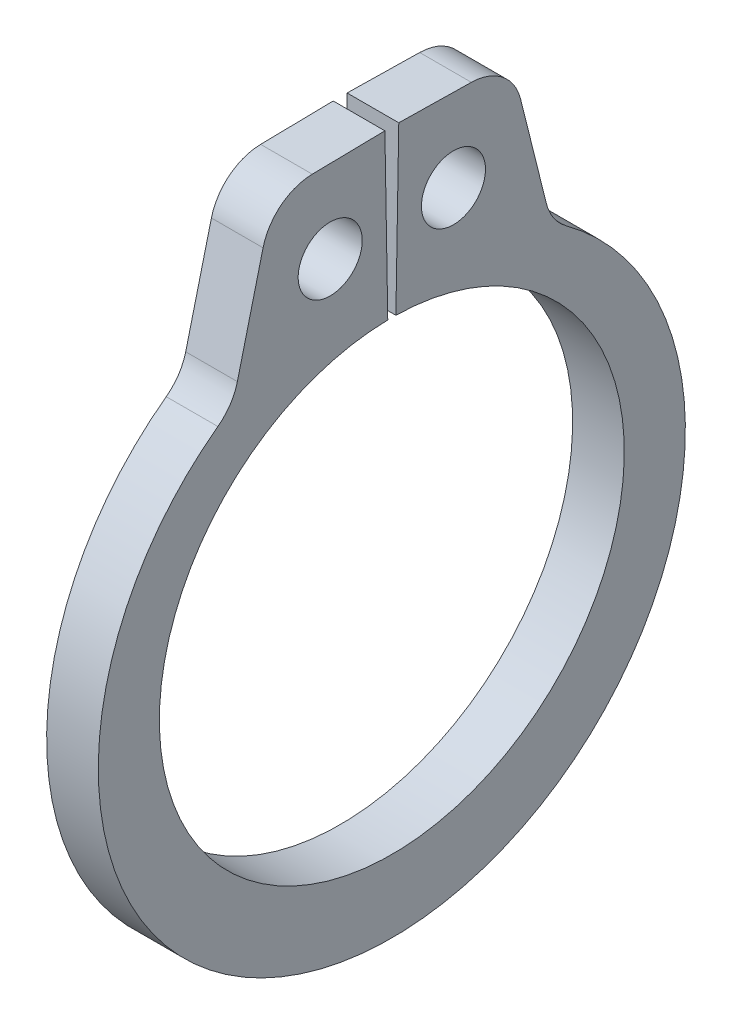
SolidWorks part; units mm, degrees
ref_plane "Front" through (0, 0, 0) normal (0, 0, 1) x (1, 0, 0)
ref_plane "Top" through (0, 0, 0) normal (0, 1, 0) x (1, 0, 0)
ref_plane "Right" through (0, 0, 0) normal (1, 0, 0) x (0, 0, -1)
sketch "Sketch1" plane through (0, 0, 0) normal (1, 0, 0) x (0, 0, -1)
  line L0 (0, 0) -> (0, 2.8575) construction
  line L1 (-0.0499, 2.8571) -> (-0.0853, 4.8888)
  line L2 (-0.0853, 4.8888) -> (-1.4649, 4.8647) construction
  line L3 (-1.4649, 4.8647) -> (-1.9565, 2.893) construction
  line L4 (0.0853, 4.8888) -> (0.0499, 2.8571)
  line L5 (0.0853, 4.8888) -> (1.4649, 4.8647) construction
  line L6 (1.4649, 4.8647) -> (1.9565, 2.893) construction
  line L7 (-1.9565, 2.893) -> (-1.6008, 2.367) construction
  line L8 (1.9565, 2.893) -> (1.6008, 2.367) construction
  line L9 (0, -2.8575) -> (0, -3.7465) construction
  line L10 (-1.4649, 4.8647) -> (-0.0499, 2.8571) construction
  line L11 (-2.8575, 0) -> (2.8575, 0) construction
  line L12 (0, 2.8575) -> (0, 4.8895) construction
  line L13 (1.4649, 4.8647) -> (1.9565, 2.893)
  line L14 (-1.4649, 4.8647) -> (-1.9565, 2.893)
  line L15 (0.0853, 4.8888) -> (1.4649, 4.8647)
  line L16 (-0.0853, 4.8888) -> (-1.4649, 4.8647)
  circle A0 centre (0, 0) radius 2.8575 construction
  arc A1 (-0.0499, 2.8571) -> (0.0499, 2.8571) centre (0, 0) ccw
  circle A2 centre (0, -0.1385) radius 3.608 construction
  circle A3 centre (0, 0) radius 4.699 construction
  circle A4 centre (-0.7574, 3.8609) radius 0.3937
  circle A5 centre (0.7574, 3.8609) radius 0.3937
  arc A6 (-1.9565, 2.893) -> (1.9565, 2.893) centre (0, -0.1385) ccw
  dimension "D1" = 15
  dimension "A" = 5.715
  dimension "L" = 9.398
  dimension "Hole" = 0.7874
  dimension "Smin" = 0.635
  dimension "Smax" = 0.889
  dimension "H" = 2.032
  dimension "Angle" = 1
extrude "Extrude1" add sketch "Sketch1" along normal mid plane 0.635
fillet "Fillet1" radius 0.635 4 edges at (0, 2.893, 1.9565) (0, 2.893, -1.9565) (0, 4.8647, -1.4649) (0, 4.8647, 1.4649)
sketch "Sketch2" plane through (0, 0, 0) normal (0, 0, 1) x (1, 0, 0)
  line L0 (-1.905, 0) -> (5.715, 0)
  line L1 (5.715, 0) -> (5.715, -3.175)
  line L3 (5.715, -3.175) -> (0.381, -3.175)
  line L4 (0.381, -3.175) -> (0.381, -2.921)
  line L5 (0.381, -2.921) -> (-0.381, -2.921)
  line L6 (-0.381, -2.921) -> (-0.381, -3.175)
  line L7 (-0.381, -3.175) -> (-1.905, -3.175) construction
  line L8 (-1.905, -3.175) -> (-1.905, 0) construction
  line L9 (0, -2.921) -> (0, 0) construction
  line L10 (5.715, 0) -> (14.0551, 0) construction
  line L11 (-0.381, -3.175) -> (-1.778, -3.175)
  line L12 (-1.778, -3.175) -> (-1.905, -3.048)
  line L13 (-1.905, -3.048) -> (-1.905, 0)
  point P14 (-0.381, -3.048)
  dimension "D2" = 7.62
  dimension "D3" = 1.905
  dimension "D4" = 45
revolve "Revolve1" [suppressed] add sketch "Sketch2" angle 360 about L10
equation "\"D2@Sketch2\" = \"W@Sketch2\"*10"
equation "\"D3@Sketch2\" = \"D2@Sketch2\"/4"
equation "\"D1@Fillet1\" = \"D1@Extrude1\""
